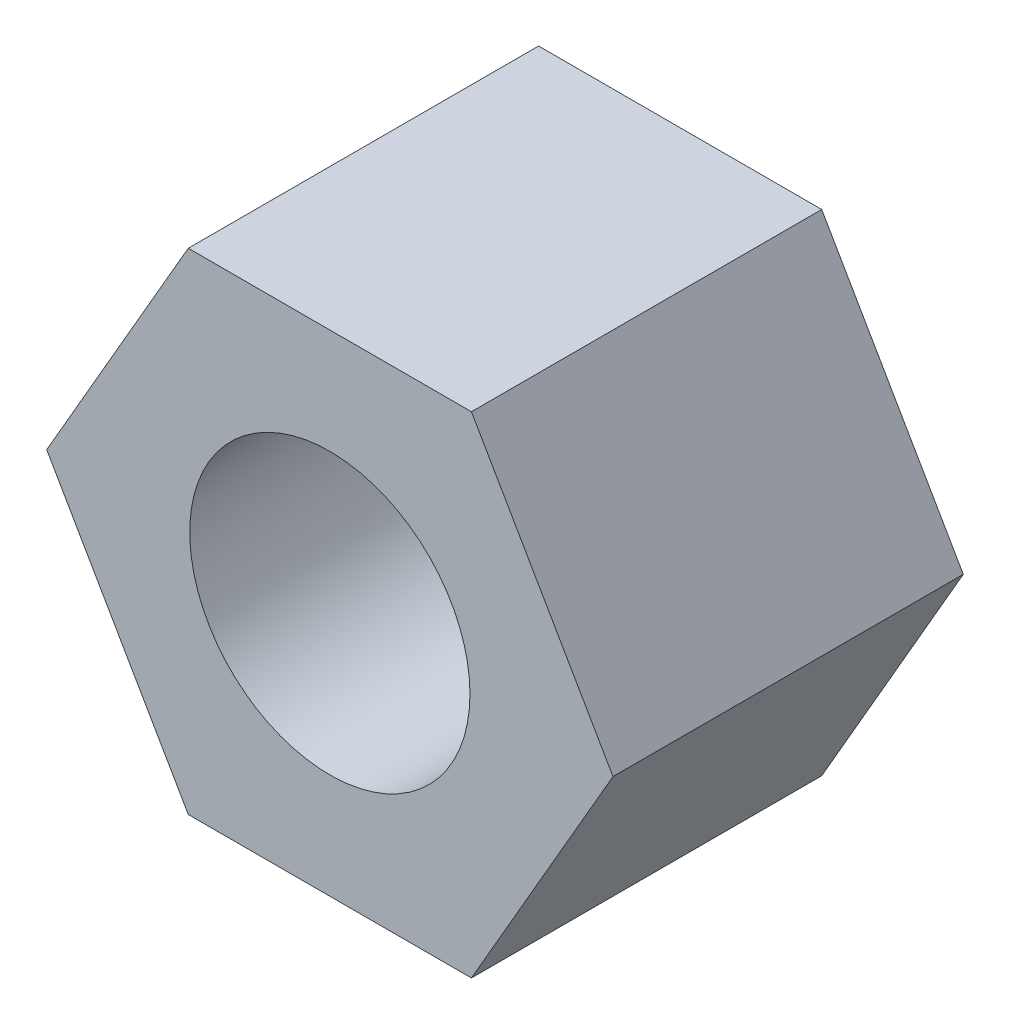
SolidWorks part; units mm, degrees
ref_plane "Front" through (0, 0, 0) normal (0, 0, 1) x (1, 0, 0)
ref_plane "Top" through (0, 0, 0) normal (0, 1, 0) x (1, 0, 0)
ref_plane "Right" through (0, 0, 0) normal (1, 0, 0) x (0, 0, -1)
sketch "Эскиз1" plane through (0, 0, 0) normal (0, 0, 1) x (1, 0, 0)
  line L1 (-2.0207, 3.5) -> (-4.0415, 0)
  line L2 (-4.0415, 0) -> (-2.0207, -3.5)
  line L3 (-2.0207, -3.5) -> (2.0207, -3.5)
  line L4 (2.0207, -3.5) -> (4.0415, 0)
  line L5 (4.0415, 0) -> (2.0207, 3.5)
  line L6 (2.0207, 3.5) -> (-2.0207, 3.5)
  circle A0 centre (0, 0) radius 3.5 construction
  circle A1 centre (0, 0) radius 2
  dimension "D1" = 4
  dimension "D2" = 7
extrude "Гайка_М4" add sketch "Эскиз1" along normal blind 5
